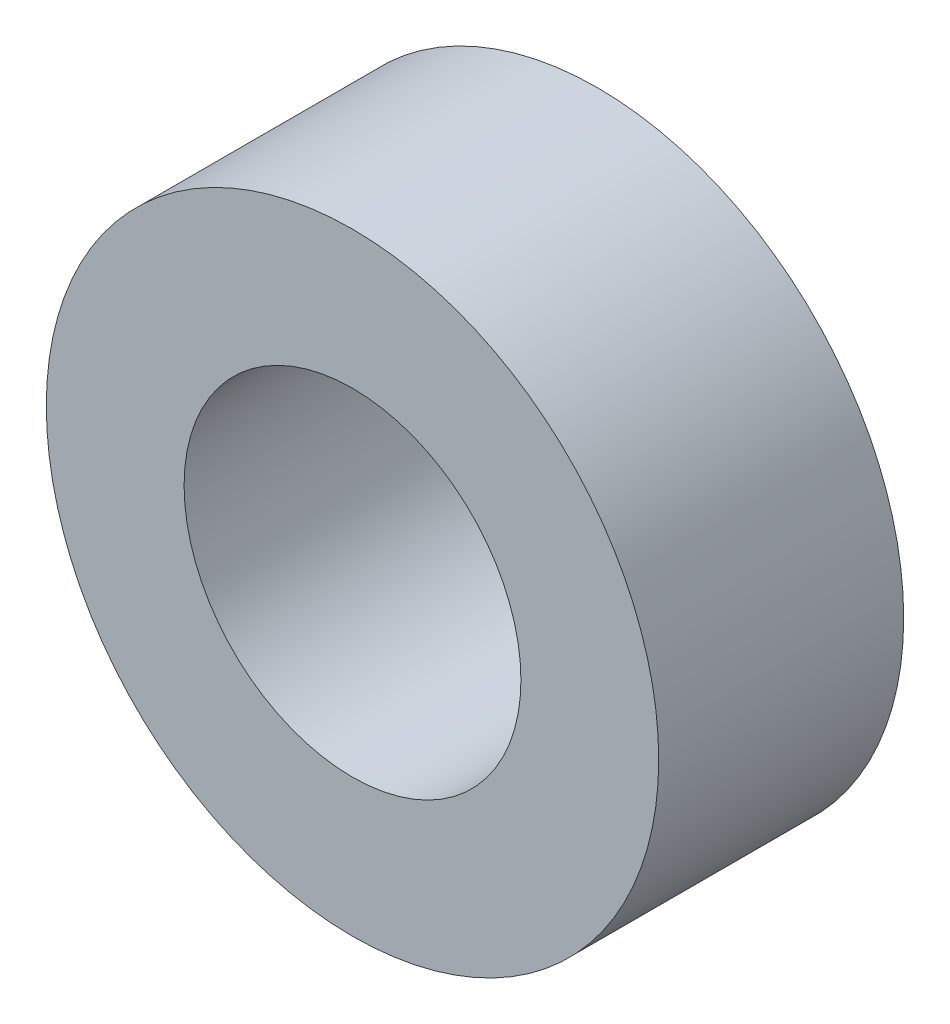
SolidWorks part; units mm, degrees
ref_plane "Front Plane" through (0, 0, 0) normal (0, 0, 1) x (1, 0, 0)
ref_plane "Top Plane" through (0, 0, 0) normal (0, 1, 0) x (1, 0, 0)
ref_plane "Right Plane" through (0, 0, 0) normal (1, 0, 0) x (0, 0, -1)
sketch "Sketch1" plane through (0, 0, 0) normal (0, 0, 1) x (1, 0, 0)
  circle A0 centre (0, 0) radius 2.75
  circle A1 centre (0, 0) radius 5
  dimension "D1" = 5.5
  dimension "D2" = 10
extrude "Boss-Extrude1" add sketch "Sketch1" along normal blind 4
